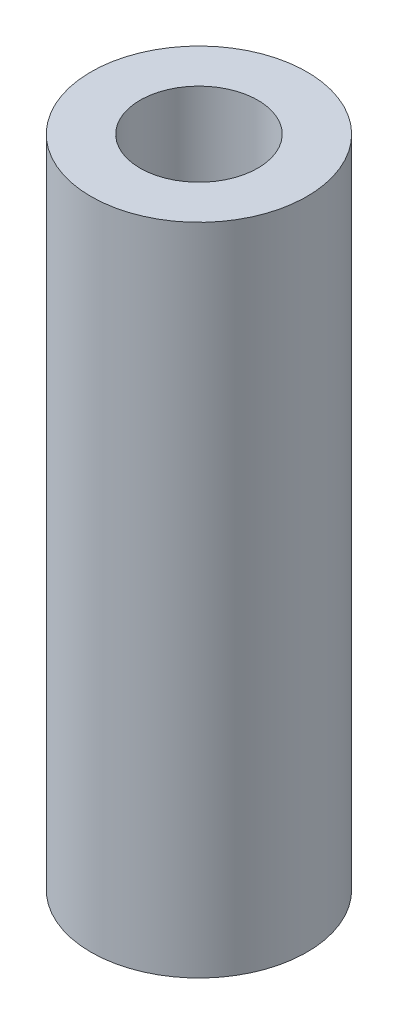
SolidWorks part; units mm, degrees
ref_plane "Front Plane" through (0, 0, 0) normal (0, 0, 1) x (1, 0, 0)
ref_plane "Top Plane" through (0, 0, 0) normal (0, 1, 0) x (1, 0, 0)
ref_plane "Right Plane" through (0, 0, 0) normal (1, 0, 0) x (0, 0, -1)
sketch "Sketch1" plane through (0, 0, 0) normal (0, 1, 0) x (1, 0, 0)
  circle A0 centre (0, 0) radius 1.8
  circle A1 centre (0, 0) radius 3.3
  dimension "D1" = 3.6
  dimension "D2" = 6.6
extrude "Boss-Extrude1" add sketch "Sketch1" along normal blind 20
